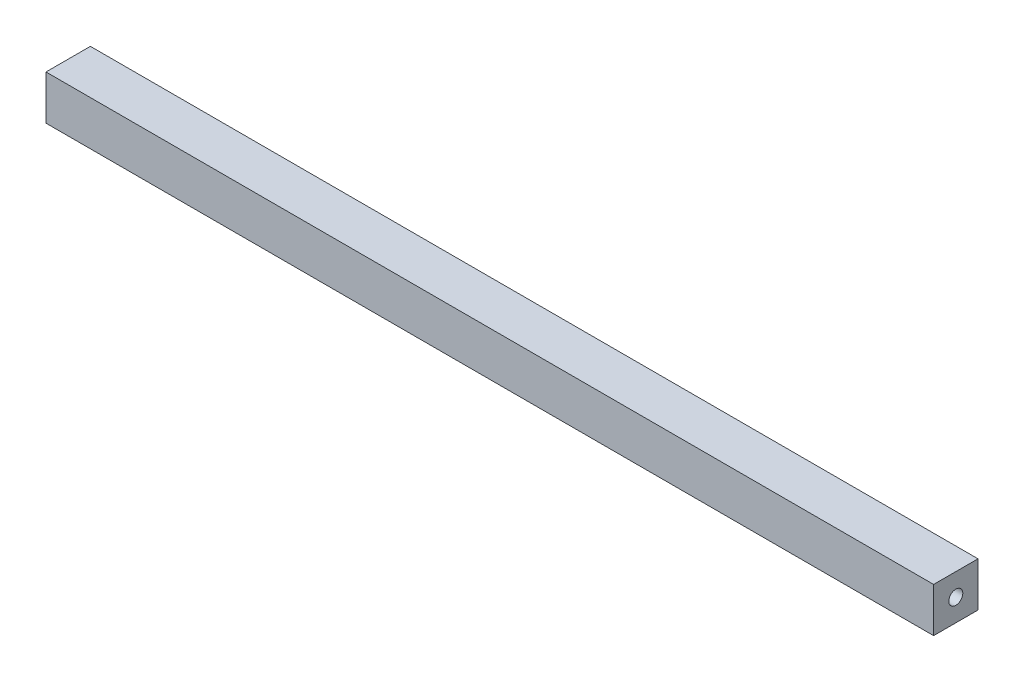
SolidWorks part; units mm, degrees
ref_plane "Front Plane" through (0, 0, 0) normal (0, 0, 1) x (1, 0, 0)
ref_plane "Top Plane" through (0, 0, 0) normal (0, 1, 0) x (1, 0, 0)
ref_plane "Right Plane" through (0, 0, 0) normal (1, 0, 0) x (0, 0, -1)
sketch "Sketch1" plane through (0, 0, 0) normal (0, 0, 1) x (1, 0, 0)
  line L1 (-254, 12.7) -> (254, 12.7)
  line L2 (-254, 12.7) -> (-254, -12.7)
  line L3 (-254, -12.7) -> (254, -12.7)
  line L4 (254, 12.7) -> (254, -12.7)
  line L5 (-254, 12.7) -> (254, -12.7) construction
  line L6 (-254, -12.7) -> (254, 12.7) construction
  point P0 (0, 0)
  dimension "D1" = 508
  dimension "D2" = 25.4
extrude "Boss-Extrude1" add sketch "Sketch1" along normal blind 25.4
sketch "Sketch2" plane through (-254, 0, 0) normal (-1, 0, 0) x (0, 0, 1)
  circle A0 centre (12.7, 0) radius 4.0005
  dimension "D1" = 8.001
extrude "Cut-Extrude1" cut sketch "Sketch2" against normal through all
